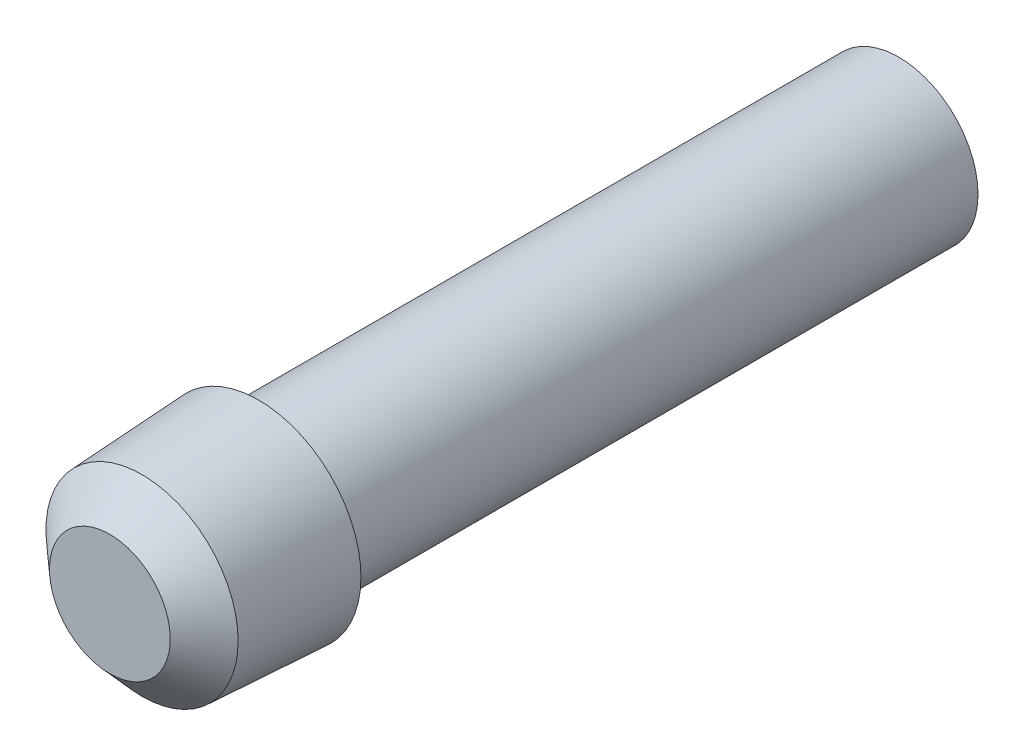
SolidWorks part; units mm, degrees
material "PET"
ref_plane "Front Plane" through (0, 0, 0) normal (0, 0, 1) x (1, 0, 0)
ref_plane "Top Plane" through (0, 0, 0) normal (0, 1, 0) x (1, 0, 0)
ref_plane "Right Plane" through (0, 0, 0) normal (1, 0, 0) x (0, 0, -1)
sketch "Sketch1" plane through (0, 0, 0) normal (0, 0, 1) x (1, 0, 0)
  circle A0 centre (0, 6.0097) radius 0.7 construction
  circle A1 centre (0, 6.0097) radius 0.7
  circle A3 centre (0, 6.0097) radius 1.25
  dimension "D1" = 2.5
extrude "Boss-Extrude1" add sketch "Sketch1" along normal up to surface (12.45 mm away)
draft "Draft1" type of draft neutral plane draft angle 2 faces to draft 1 face at (0.7, 6.0097, 0) neutral plane through (0, 6.0097, 0) neutral plane normal (0, 0, -1) reverse direction yes parameters "D1"=2
sketch "Sketch2" plane through (0, 0, 12.45) normal (0, 0, 1) x (1, 0, 0)
  circle A1 centre (0, 6.0097) radius 1.25
  circle A2 centre (0, 6.0097) radius 1.25
  dimension "D1" = 0
extrude "Boss-Extrude2" add sketch "Sketch2" against normal blind 3.175
sketch "Sketch3" plane through (0, 0, 12.45) normal (0, 0, 1) x (1, 0, 0)
  circle A0 centre (0, 6.0097) radius 1.6129
  circle A1 centre (0, 6.0097) radius 1.25
  circle A2 centre (0, 6.0097) radius 1.25
  dimension "D2" = 3.2258
  dimension "D1" = 0
extrude "Boss-Extrude3" add sketch "Sketch3" against normal blind 2.3495
draft "Draft2" type of draft neutral plane draft angle 3 faces to draft 1 face at (1.6129, 6.0097, 10.1005) neutral plane through (0, 6.0097, 10.1005) neutral plane normal (0, 0, -1) reverse direction yes parameters "D1"=3
chamfer "Chamfer1" distance 0.508 angle 45 1 edges at (0.7, 6.0097, 0)
chamfer "Chamfer2" distance 0.508 angle 45 1 edges at (0, 4.5199, 12.45)
